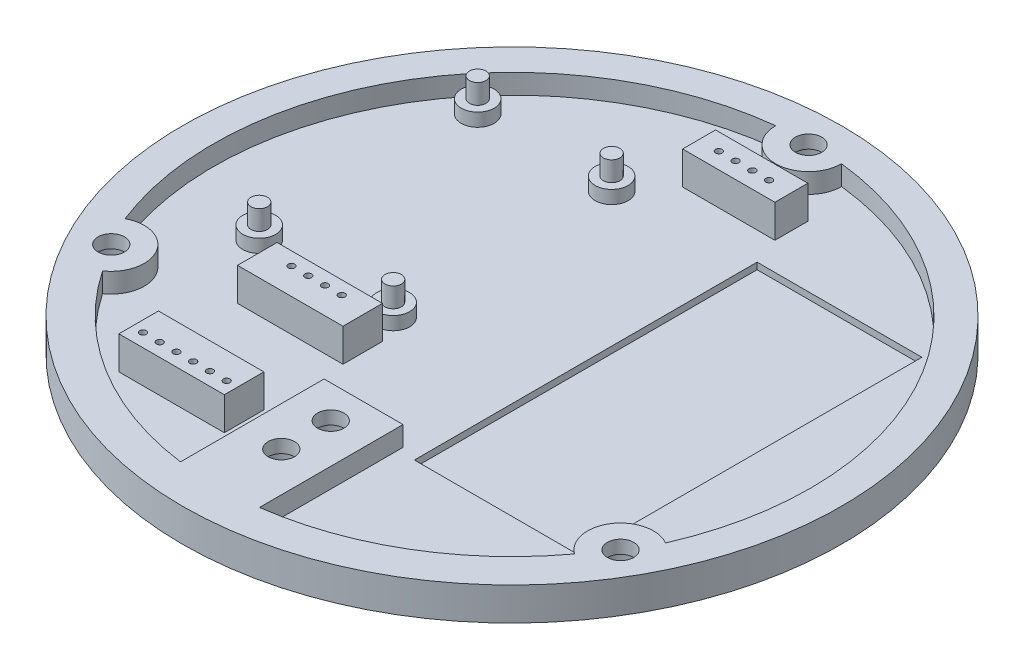
SolidWorks part; units mm, degrees
ref_plane "Ebene vorne" through (0, 0, 0) normal (0, 0, 1) x (1, 0, 0)
ref_plane "Ebene oben" through (0, 0, 0) normal (0, 1, 0) x (1, 0, 0)
ref_plane "Ebene rechts" through (0, 0, 0) normal (1, 0, 0) x (0, 0, -1)
sketch "Skizze2" plane through (0, 0, 0) normal (0, 1, 0) x (1, 0, 0)
  line L0 (0, 0) -> (43.3013, -25) construction
  line L1 (0, 0) -> (-44.2239, -23.3291) construction
  line L2 (0, 45) -> (0, -45) construction
  circle A0 centre (0, 0) radius 50
  circle A1 centre (0, 0) radius 45
  circle A2 centre (38.9711, -22.5) radius 2
  circle A3 centre (-39.8015, -20.9962) radius 2
  circle A4 centre (0, 45) radius 2
  circle A5 centre (0, -35) radius 2
  circle A6 centre (0, -27.5) radius 2
  dimension "D1" = 100
  dimension "D2" = 90
extrude "Aufsatz-Linear austragen1" add sketch "Skizze2" along normal blind 5 contours A4 A1 A3 A2 A6 A5 | A0 A4 A1 A2 A3
sketch "Skizze9" plane through (0, 5, 0) normal (0, 1, 0) x (1, 0, 0)
  line L2 (-6, -39.5312) -> (-6, -22.5312)
  line L3 (-6, -22.5312) -> (6, -22.5312)
  line L4 (6, -39.5312) -> (6, -22.5312)
  arc A0 (-6, -39.5312) -> (6, -39.5312) centre (0, 0) cw
  point P4 (0, -27.5)
extrude "Schnitt-Linear austragen2" cut sketch "Skizze9" against normal blind 3
sketch "Skizze10" plane through (0, 0, 0) normal (0, -1, 0) x (1, 0, 0)
  circle A0 centre (0, 27.5) radius 3.5
  circle A1 centre (0, 35) radius 3.5
  circle A2 centre (38.9711, 22.5) radius 3.5
  circle A3 centre (-39.8015, 20.9962) radius 3.5
  circle A4 centre (0, -45) radius 3.5
extrude "Schnitt-Linear austragen3" cut sketch "Skizze10" against normal blind 3
sketch "Skizze11" plane through (0, 5, 0) normal (0, 1, 0) x (1, 0, 0)
  line L0 (-5.979, -44.3198) -> (-5.979, -22.5)
  line L1 (-5.979, -22.5) -> (6, -22.5312)
  line L2 (6, -22.5312) -> (6, -44.317)
  arc A0 (-42.1344, -16.5738) -> (-36.9916, -25.132) centre (-39.8015, -20.9962) cw
  arc A1 (41.4711, -18.1699) -> (36.0055, -26.5255) centre (38.9711, -22.5) ccw
  arc A2 (5, 45) -> (-5, 45) centre (0, 45) cw
  arc A3 (5, 45) -> (41.4711, -18.1699) centre (0, 0) cw
  arc A4 (-5, 45) -> (-42.1344, -16.5738) centre (0, 0) ccw
  arc A5 (-36.9916, -25.132) -> (-5.979, -44.3198) centre (0, 0) ccw
  arc A6 (36.0055, -26.5255) -> (6, -44.317) centre (0, 0) cw
extrude "Schnitt-Linear austragen7" cut sketch "Skizze11" against normal blind 3
sketch "Skizze12" plane through (0, 2, 0) normal (0, 1, 0) x (1, 0, 0)
  circle A1 centre (-32.1557, 26.9561) radius 2.5
  circle A2 centre (-11.8357, 26.9561) radius 2.5
  circle A3 centre (-32.1557, -6.1939) radius 2.5
  circle A4 centre (-11.8357, -6.1939) radius 2.5
ref_plane "Ebene1" through (0, 7, 0) normal (0, 1, 0) x (1, 0, 0)
sketch "Skizze27" plane through (0, 2, 0) normal (0, -1, 0) x (1, 0, 0)
  line L1 (33.52, -28.668) -> (8.52, -28.668)
  line L2 (33.52, -28.668) -> (33.52, 23.332)
  line L3 (33.52, 23.332) -> (8.52, 23.332)
  line L4 (8.52, -28.668) -> (8.52, 23.332)
  dimension "D1" = 52
  dimension "D2" = 25
extrude "Schnitt-Linear austragen10" cut sketch "Skizze27" along normal blind 1
extrude "Aufsatz-Linear austragen5" add sketch "Skizze12" along normal blind 2
sketch "Skizze30" plane through (0, 4, 0) normal (0, 1, 0) x (1, 0, 0)
  circle A0 centre (-32.1557, 26.9561) radius 1.25
  circle A1 centre (-11.8357, 26.9561) radius 1.25
  circle A2 centre (-32.1557, -6.1939) radius 1.25
  circle A3 centre (-11.8357, -6.1939) radius 1.25
extrude "Aufsatz-Linear austragen6" add sketch "Skizze30" along normal blind 3
sketch "Skizze31" plane through (0, 2, 0) normal (0, 1, 0) x (1, 0, 0)
  line L5 (-25.4775, -10.1664) -> (-9.4775, -10.1664)
  line L6 (-25.4775, -10.1664) -> (-25.4775, -16.1664)
  line L7 (-25.4775, -16.1664) -> (-9.4775, -16.1664)
  line L8 (-9.4775, -10.1664) -> (-9.4775, -16.1664)
  line L9 (-9.4775, -34.1664) -> (-25.4775, -34.1664)
  line L10 (-9.4775, -34.1664) -> (-9.4775, -28.1664)
  line L11 (-9.4775, -28.1664) -> (-25.4775, -28.1664)
  line L12 (-25.4775, -34.1664) -> (-25.4775, -28.1664)
extrude "Aufsatz-Linear austragen8" add sketch "Skizze31" along normal blind 5
sketch "Skizze32" plane through (0, 7, 0) normal (0, 1, 0) x (1, 0, 0)
  line L0 (-17.4775, -10.1664) -> (-17.4775, -34.1664) construction
  line L1 (-16.2075, -12.1664) -> (-16.2075, -32.1664) construction
  line L2 (-16.2075, -32.1664) -> (-13.6675, -32.1664) construction
  line L3 (-9.4775, -10.1664) -> (-25.4775, -10.1664) construction
  line L4 (-25.4775, -34.1664) -> (-9.4775, -34.1664) construction
  line L5 (-17.4775, -12.1664) -> (-16.2075, -12.1664) construction
  line L6 (-16.2075, -10.1664) -> (-16.2075, -12.1664) construction
  line L7 (-16.2075, -12.1664) -> (-13.6675, -12.1664) construction
  line L8 (-17.4775, -12.1664) -> (-18.7475, -12.1664) construction
  line L9 (-18.7475, -12.1664) -> (-21.2875, -12.1664) construction
  line L10 (-13.6675, -32.1664) -> (-11.1275, -32.1664) construction
  line L11 (-16.2075, -32.1664) -> (-18.7475, -32.1664) construction
  line L12 (-18.7475, -32.1664) -> (-21.2875, -32.1664) construction
  line L13 (-21.2875, -32.1664) -> (-23.8275, -32.1664) construction
  circle A0 centre (-16.2075, -12.1664) radius 0.5
  circle A1 centre (-13.6675, -12.1664) radius 0.5
  circle A2 centre (-18.7475, -12.1664) radius 0.5
  circle A3 centre (-21.2875, -12.1664) radius 0.5
  circle A4 centre (-16.2075, -32.1664) radius 0.5
  circle A5 centre (-13.6675, -32.1664) radius 0.5
  circle A6 centre (-11.1275, -32.1664) radius 0.5
  circle A7 centre (-18.7475, -32.1664) radius 0.5
  circle A8 centre (-21.2875, -32.1664) radius 0.5
  circle A9 centre (-23.8275, -32.1664) radius 0.5
extrude "Schnitt-Linear austragen11" cut sketch "Skizze32" against normal blind 6.5
sketch "Skizze34" plane through (0, 2, 0) normal (0, 1, 0) x (1, 0, 0)
  line L0 (0, -35) -> (0, -39.5) construction
  line L1 (0, 18.5) -> (6.35, 18.5) construction
  line L2 (0, 18.5) -> (0, 14) construction
  line L3 (0, 14) -> (0, 6.5) construction
  line L4 (0, 4.5) -> (0, -27.5) construction
  line L5 (0, 18.5) -> (-6.35, 18.5) construction
  line L6 (-6.35, 18.5) -> (-6.35, -39.5) construction
  line L7 (-6.35, -39.5) -> (0, -39.5) construction
  line L8 (0, -39.5) -> (6.35, -39.5) construction
  line L9 (6.35, -39.5) -> (6.35, 18.5) construction
  circle A0 centre (0, 14) radius 2 construction
  circle A1 centre (0, 6.5) radius 2 construction
sketch "Skizze35" plane through (0, 2, 0) normal (0, 1, 0) x (1, 0, 0)
  line L2 (-7, 37.8858) -> (7, 37.8858)
  line L3 (-7, 37.8858) -> (-7, 32.8858)
  line L4 (-7, 32.8858) -> (7, 32.8858)
  line L5 (7, 37.8858) -> (7, 32.8858)
  line L6 (-7, 37.8858) -> (7, 32.8858) construction
  line L7 (-7, 32.8858) -> (7, 37.8858) construction
  point P5 (0, 35.3858)
extrude "Aufsatz-Linear austragen9" add sketch "Skizze35" along normal blind 5
sketch "Skizze36" plane through (0, 7, 0) normal (0, 1, 0) x (1, 0, 0)
  line L2 (-0.1516, 35.3392) -> (1.1184, 35.3392) construction
  line L4 (1.1184, 35.3392) -> (3.6584, 35.3392) construction
  line L5 (-0.1516, 35.3392) -> (-1.4216, 35.3392) construction
  line L6 (-1.4216, 35.3392) -> (-3.9616, 35.3392) construction
  circle A0 centre (1.1184, 35.3392) radius 0.5
  circle A1 centre (3.6584, 35.3392) radius 0.5
  circle A2 centre (-1.4216, 35.3392) radius 0.5
  circle A3 centre (-3.9616, 35.3392) radius 0.5
extrude "Schnitt-Linear austragen12" cut sketch "Skizze36" against normal blind 6.5
